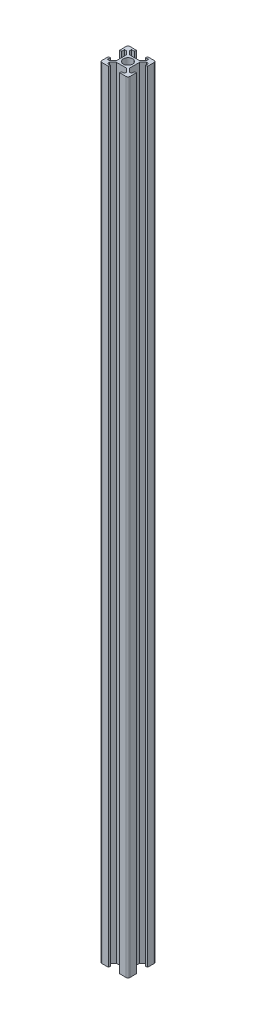
SolidWorks part; units mm, degrees
ref_plane "Front Plane" through (0, 0, 0) normal (0, 0, 1) x (1, 0, 0)
ref_plane "Top Plane" through (0, 0, 0) normal (0, 1, 0) x (1, 0, 0)
ref_plane "Right Plane" through (0, 0, 0) normal (1, 0, 0) x (0, 0, -1)
sketch "Sketch1" plane through (0, 0, 0) normal (0, 1, 0) x (1, 0, 0)
  line L0 (-7.5, -3) -> (-7.5, -6.5)
  line L5 (-6.5, -7.5) -> (-3, -7.5)
  line L6 (-7.5, -3) -> (-6.5, -3)
  line L7 (-3, -7.5) -> (-3, -6.5)
  line L8 (-6.5, -3) -> (-6.5, -4.6)
  line L9 (-3, -6.5) -> (-4.6, -6.5)
  line L10 (-6.5, -4.6) -> (-5.3071, -4.6)
  line L11 (-4.6, -6.5) -> (-4.6, -5.3071)
  line L13 (-3.5071, 0) -> (-3.5071, -2.8)
  line L14 (-3.5071, -2.8) -> (-5.3071, -4.6)
  line L16 (0, -3.5071) -> (-2.8, -3.5071)
  line L17 (-2.8, -3.5071) -> (-4.6, -5.3071)
  line L18 (-3.5071, 2.8) -> (-5.3071, 4.6)
  line L19 (-6.5, 4.6) -> (-5.3071, 4.6)
  line L20 (-6.5, 3) -> (-6.5, 4.6)
  line L21 (-7.5, 3) -> (-6.5, 3)
  line L22 (-7.5, 6.5) -> (-7.5, 3)
  line L23 (-3, 7.5) -> (-6.5, 7.5)
  line L24 (-3, 7.5) -> (-3, 6.5)
  line L25 (-3, 6.5) -> (-4.6, 6.5)
  line L26 (-4.6, 6.5) -> (-4.6, 5.3071)
  line L27 (-2.8, 3.5071) -> (-4.6, 5.3071)
  line L28 (0, 3.5071) -> (-2.8, 3.5071)
  line L31 (-3.5071, 0) -> (-3.5071, 2.8)
  line L32 (2.8, 3.5071) -> (4.6, 5.3071)
  line L33 (4.6, 6.5) -> (4.6, 5.3071)
  line L34 (3, 6.5) -> (4.6, 6.5)
  line L35 (3, 7.5) -> (3, 6.5)
  line L36 (6.5, 7.5) -> (3, 7.5)
  line L37 (7.5, 3) -> (7.5, 6.5)
  line L38 (7.5, 3) -> (6.5, 3)
  line L39 (6.5, 3) -> (6.5, 4.6)
  line L40 (6.5, 4.6) -> (5.3071, 4.6)
  line L41 (3.5071, 2.8) -> (5.3071, 4.6)
  line L42 (3.5071, 0) -> (3.5071, 2.8)
  line L45 (0, 3.5071) -> (2.8, 3.5071)
  line L46 (3.5071, -2.8) -> (5.3071, -4.6)
  line L47 (6.5, -4.6) -> (5.3071, -4.6)
  line L48 (6.5, -3) -> (6.5, -4.6)
  line L49 (7.5, -3) -> (6.5, -3)
  line L50 (7.5, -6.5) -> (7.5, -3)
  line L51 (3, -7.5) -> (6.5, -7.5)
  line L52 (3, -7.5) -> (3, -6.5)
  line L53 (3, -6.5) -> (4.6, -6.5)
  line L54 (4.6, -6.5) -> (4.6, -5.3071)
  line L55 (2.8, -3.5071) -> (4.6, -5.3071)
  line L56 (0, -3.5071) -> (2.8, -3.5071)
  line L59 (3.5071, 0) -> (3.5071, -2.8)
  arc A1 (-6.5, -7.5) -> (-7.5, -6.5) centre (-6.5, -6.5) cw
  arc A2 (-2.5, 0) -> (0, -2.5) centre (0, 0) ccw
  arc A3 (-7.5, 6.5) -> (-6.5, 7.5) centre (-6.5, 6.5) cw
  arc A4 (0, 2.5) -> (-2.5, 0) centre (0, 0) ccw
  arc A5 (6.5, 7.5) -> (7.5, 6.5) centre (6.5, 6.5) cw
  arc A6 (2.5, 0) -> (0, 2.5) centre (0, 0) ccw
  arc A7 (7.5, -6.5) -> (6.5, -7.5) centre (6.5, -6.5) cw
  arc A8 (0, -2.5) -> (2.5, 0) centre (0, 0) ccw
  point P8 (-7.5, -3)
  point P9 (-3, -7.5)
  point P75 (0, 0)
  dimension "D1" = 1
  dimension "D9" = 2.5
  dimension "D2" = 3
  dimension "D3" = 7.5
  dimension "D4" = 3
  dimension "D5" = 1
  dimension "D6" = 1
  dimension "D7" = 1.6
  dimension "D8" = 2.8
  dimension "D10" = 1
  dimension "D11" = 4
extrude "Boss-Extrude1" add sketch "Sketch1" along normal blind 420
